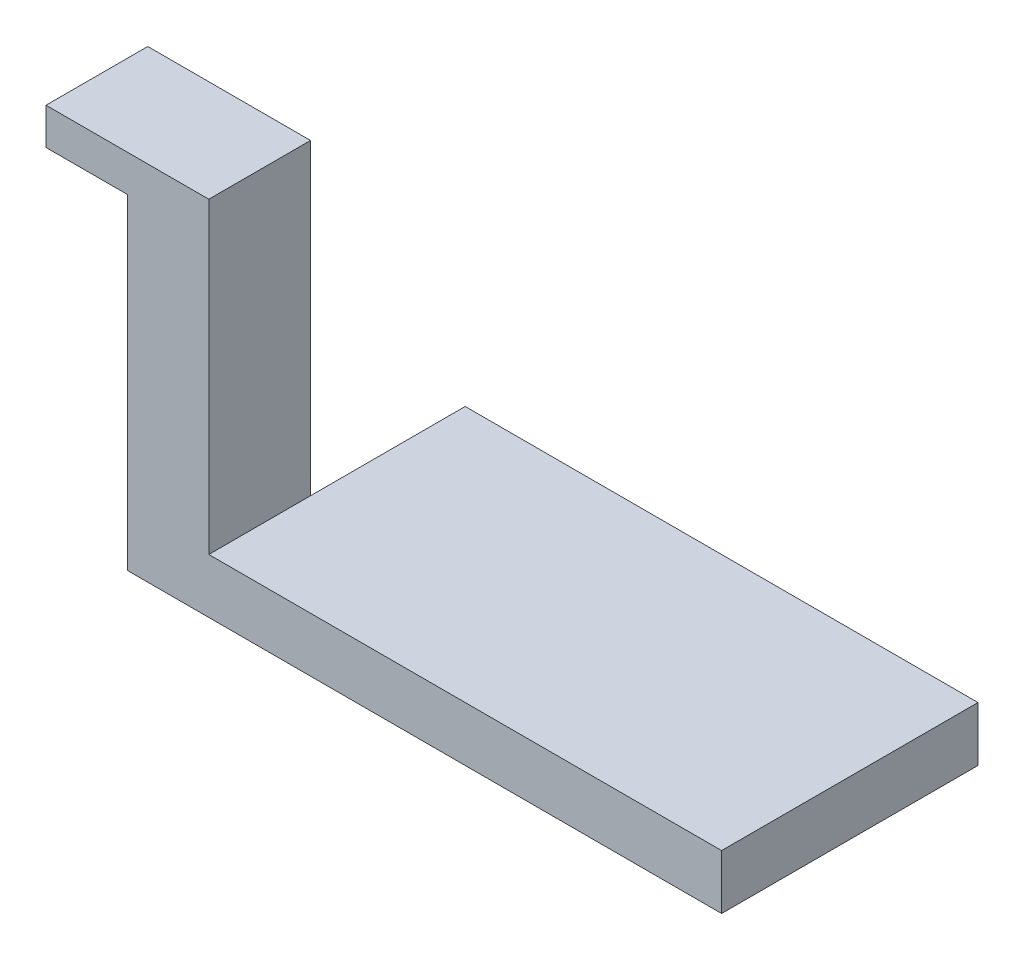
SolidWorks part; units mm, degrees
ref_plane "Front Plane" through (0, 0, 0) normal (0, 0, 1) x (1, 0, 0)
ref_plane "Top Plane" through (0, 0, 0) normal (0, 1, 0) x (1, 0, 0)
ref_plane "Right Plane" through (0, 0, 0) normal (1, 0, 0) x (0, 0, -1)
sketch "Sketch1" plane through (0, 0, 0) normal (0, 1, 0) x (1, 0, 0)
  line L1 (0, 0) -> (10.16, 0)
  line L2 (0, 0) -> (0, 6.35)
  line L3 (0, 6.35) -> (10.16, 6.35)
  line L4 (10.16, 0) -> (10.16, 6.35)
  dimension "D1" = 6.35
  dimension "D2" = 10.16
extrude "Boss-Extrude1" add sketch "Sketch1" along normal blind 2.286
sketch "Sketch2" plane through (0, 0, 0) normal (-1, 0, 0) x (0, 0, 1)
  line L0 (-6.35, 2.286) -> (0, 2.286) construction
  line L1 (-6.0452, 1.9812) -> (-0.2032, 1.9812)
  line L2 (-6.0452, 1.9812) -> (-6.0452, 0.3302)
  line L3 (-6.0452, 0.3302) -> (-0.2032, 0.3302)
  line L4 (-0.2032, 1.9812) -> (-0.2032, 0.3302)
  line L5 (-6.35, 2.286) -> (-6.35, 0) construction
  dimension "D1" = 5.842
  dimension "D2" = 1.651
  dimension "D3" = 0.3048
  dimension "D4" = 0.3048
extrude "Cut-Extrude1" cut sketch "Sketch2" against normal blind 8.89
sketch "Sketch3" plane through (0, 0, 0) normal (0, -1, 0) x (1, 0, 0)
  line L0 (0, 0) -> (10.16, 0) construction
  line L1 (10.16, -6.35) -> (5.08, -6.35)
  line L2 (10.16, -6.35) -> (10.16, 0)
  line L3 (10.16, 0) -> (5.08, 0)
  line L4 (5.08, -6.35) -> (5.08, 0)
  dimension "D1" = 5.08
extrude "Boss-Extrude2" add sketch "Sketch3" along normal blind 20.32
sketch "Sketch4" plane through (10.16, 0, 0) normal (1, 0, 0) x (0, 0, -1)
  line L0 (6.35, -20.32) -> (0, -20.32) construction
  line L1 (16.002, -20.32) -> (0, -20.32)
  line L2 (16.002, -20.32) -> (16.002, -16.9164)
  line L3 (16.002, -16.9164) -> (0, -16.9164)
  line L4 (0, -20.32) -> (0, -16.9164)
  line L5 (0, 2.286) -> (0, -20.32) construction
  dimension "D1" = 16.002
  dimension "D2" = 0
  dimension "D3" = 3.4036
  dimension "D4" = 90
  dimension "D5" = 0
extrude "Boss-Extrude3" add sketch "Sketch4" along normal blind 32.004
